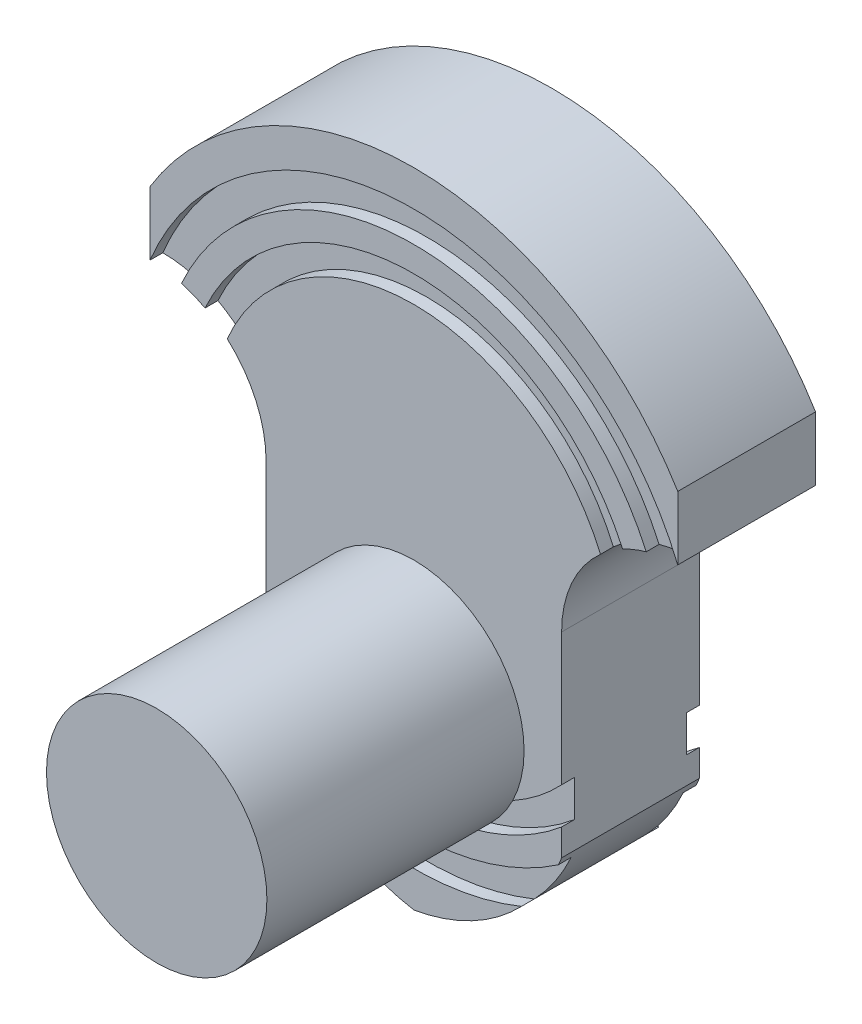
SolidWorks part; units mm, degrees
ref_plane "Front Plane" through (0, 0, 0) normal (0, 0, 1) x (1, 0, 0)
ref_plane "Top Plane" through (0, 0, 0) normal (0, 1, 0) x (1, 0, 0)
ref_plane "Right Plane" through (0, 0, 0) normal (1, 0, 0) x (0, 0, -1)
sketch "Sketch2" plane through (0, 0, 0) normal (0, 0, 1) x (1, 0, 0)
  line L0 (0, -88.9) -> (0, 9.2407) construction
  line L1 (20.4293, -72.4469) -> (20.4293, -45.3998)
  line L2 (36.4911, -29.3381) -> (36.4911, -20.5324)
  line L4 (-20.4293, -72.4469) -> (-20.4293, -45.3998)
  line L5 (-36.4911, -29.3381) -> (-36.4911, -20.5324)
  arc A0 (0, -88.9) -> (-20.4293, -72.4469) centre (4.4826, -62.4244) cw
  arc A1 (-20.4293, -45.3998) -> (-36.4911, -29.3381) centre (-36.4911, -45.3998) ccw
  arc A2 (-36.4911, -20.5324) -> (0, 0) centre (0, -42.6929) cw
  arc A6 (0, -88.9) -> (20.4293, -72.4469) centre (-4.4826, -62.4244) ccw
  arc A7 (20.4293, -45.3998) -> (36.4911, -29.3381) centre (36.4911, -45.3998) cw
  arc A8 (36.4911, -20.5324) -> (0, 0) centre (0, -42.6929) ccw
  dimension "D5" = 26.8524
  dimension "D7" = 42.6929
  dimension "D4" = 26.8524
  dimension "D6" = 42.6929
  dimension "D1" = 88.9
extrude "Boss-Extrude2" add sketch "Sketch2" along normal blind 19.05
sketch "Sketch3" plane through (0, 0, 19.05) normal (0, 0, 1) x (1, 0, 0)
  line L0 (0, 0) -> (0, -44.45) construction
  circle A0 centre (0, -44.45) radius 39.4964
  circle A1 centre (0, -44.45) radius 35.26
  dimension "D1" = 44.45
extrude "Cut-Extrude2" cut sketch "Sketch3" against normal blind 1.778
sketch "Sketch4" plane through (0, 0, 19.05) normal (0, 0, 1) x (1, 0, 0)
  line L0 (0, 0) -> (0, -44.45) construction
  circle A0 centre (0, -44.45) radius 28.069
  circle A1 centre (0, -44.45) radius 31.7462
extrude "Cut-Extrude3" cut sketch "Sketch4" against normal blind 1.778
sketch "Sketch5" plane through (0, 0, 0) normal (0, 0, -1) x (-1, 0, 0)
  circle A1 centre (0, -44.45) radius 35.26
  circle A2 centre (0, -44.45) radius 35.26
  circle A3 centre (0, -44.45) radius 39.4964
  circle A4 centre (0, -44.45) radius 39.4964
  dimension "D1" = 0
  dimension "D2" = 0
extrude "Cut-Extrude4" cut sketch "Sketch5" against normal blind 1.778
sketch "Sketch7" plane through (0, 0, 0) normal (0, 0, -1) x (-1, 0, 0)
  circle A1 centre (0, -44.45) radius 31.7462
  circle A2 centre (0, -44.45) radius 31.7462
  circle A3 centre (0, -44.45) radius 28.069
  circle A4 centre (0, -44.45) radius 28.069
  dimension "D1" = 0
  dimension "D2" = 0
extrude "Cut-Extrude5" cut sketch "Sketch7" against normal blind 1.778
sketch "Sketch8" plane through (0, 0, 19.05) normal (0, 0, 1) x (1, 0, 0)
  line L0 (0, 0) -> (0, -88.9) construction
  circle A0 centre (0, -62.23) radius 15.24
  dimension "D1" = 30.48
  dimension "D2" = 62.23
extrude "Boss-Extrude3" add sketch "Sketch8" along normal blind 35.56 contours A0
